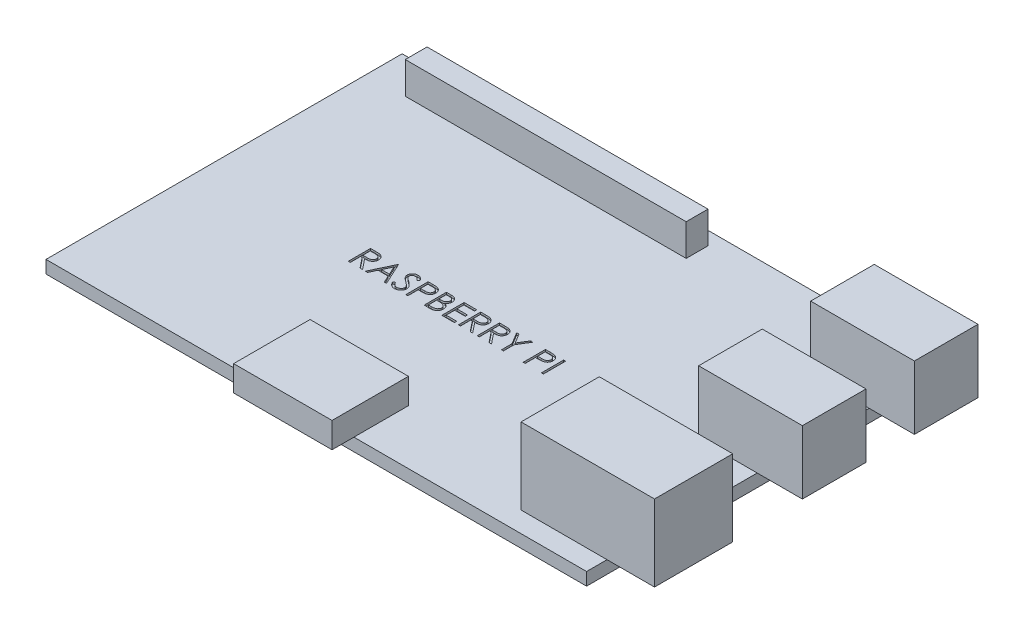
SolidWorks part; units mm, degrees
ref_plane "Front Plane" through (0, 0, 0) normal (0, 0, 1) x (1, 0, 0)
ref_plane "Top Plane" through (0, 0, 0) normal (0, 1, 0) x (1, 0, 0)
ref_plane "Right Plane" through (0, 0, 0) normal (1, 0, 0) x (0, 0, -1)
sketch "Sketch1" plane through (0, 0, 0) normal (0, 1, 0) x (1, 0, 0)
  line L1 (0, 0) -> (85, 0)
  line L2 (0, 0) -> (0, 56)
  line L3 (0, 56) -> (85, 56)
  line L4 (85, 0) -> (85, 56)
  dimension "D1" = 85
  dimension "D2" = 56
extrude "Boss-Extrude1" add sketch "Sketch1" along normal blind 2
sketch "Sketch2" plane through (0, 2, 0) normal (0, 1, 0) x (1, 0, 0)
  line L1 (6.0264, 53.8913) -> (50.1963, 53.8913)
  line L2 (6.0264, 53.8913) -> (6.0264, 50.4614)
  line L3 (6.0264, 50.4614) -> (50.1963, 50.4614)
  line L4 (50.1963, 53.8913) -> (50.1963, 50.4614)
extrude "Boss-Extrude2" add sketch "Sketch2" along normal blind 5
sketch "Sketch3" plane through (0, 2, 0) normal (0, 1, 0) x (1, 0, 0)
  line L1 (75.7947, 54.4382) -> (92.1075, 54.4382)
  line L2 (75.7947, 54.4382) -> (75.7947, 44.4382)
  line L3 (75.7947, 44.4382) -> (92.1075, 44.4382)
  line L4 (92.1075, 54.4382) -> (92.1075, 44.4382)
  line L5 (75.7947, 36.8256) -> (92.1075, 36.8256)
  line L6 (75.7947, 36.8256) -> (75.7947, 26.8256)
  line L7 (75.7947, 26.8256) -> (92.1075, 26.8256)
  line L8 (92.1075, 36.8256) -> (92.1075, 26.8256)
  dimension "D1" = 10
extrude "Boss-Extrude3" add sketch "Sketch3" along normal blind 10
sketch "Sketch4" plane through (0, 2, 0) normal (0, 1, 0) x (1, 0, 0)
  line L1 (71.4795, 15.5197) -> (92.4623, 15.5197)
  line L2 (71.4795, 15.5197) -> (71.4795, 3.2173)
  line L3 (71.4795, 3.2173) -> (92.4623, 3.2173)
  line L4 (92.4623, 15.5197) -> (92.4623, 3.2173)
extrude "Boss-Extrude4" add sketch "Sketch4" along normal blind 12
sketch "Sketch5" plane through (0, 2, 0) normal (0, 1, 0) x (1, 0, 0)
  line L1 (32.9452, 8.5716) -> (48.4151, 8.5716)
  line L2 (32.9452, 8.5716) -> (32.9452, -3.4403)
  line L3 (32.9452, -3.4403) -> (48.4151, -3.4403)
  line L4 (48.4151, 8.5716) -> (48.4151, -3.4403)
extrude "Boss-Extrude5" add sketch "Sketch5" along normal blind 4
sketch "Sketch6" plane through (0, 2, 0) normal (0, 1, 0) x (1, 0, 0)
  line L0 (23.5723, 23.5044) -> (61.246, 23.5044) construction
  text T0 "RASPBERRY PI"
extrude "Cut-Extrude1" cut sketch "Sketch6" against normal blind 0.3
